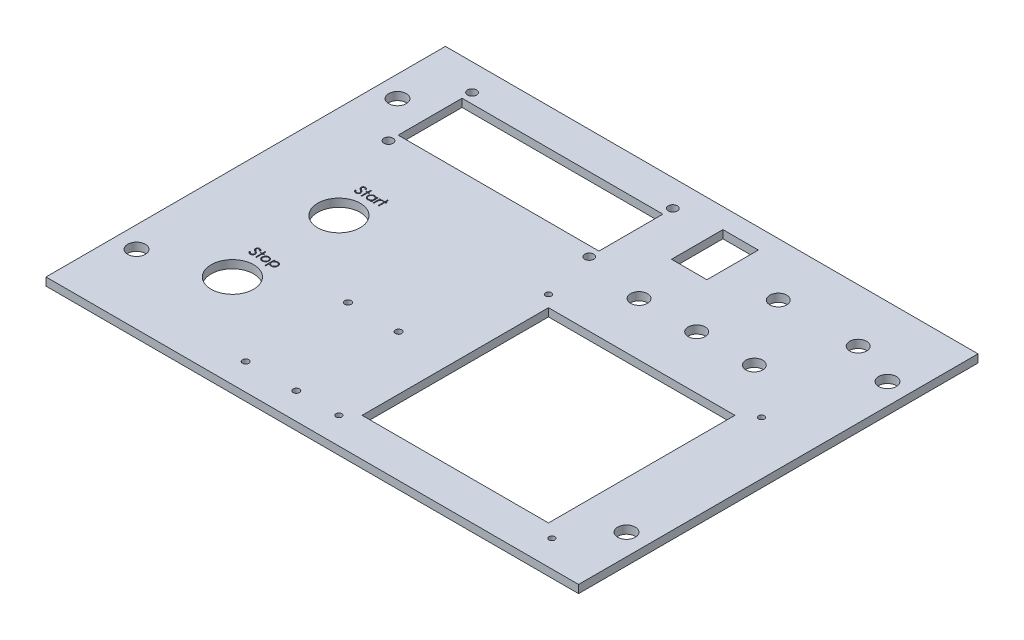
SolidWorks part; units mm, degrees
ref_plane "Front Plane" through (0, 0, 0) normal (0, 0, 1) x (1, 0, 0)
ref_plane "Top Plane" through (0, 0, 0) normal (0, 1, 0) x (1, 0, 0)
ref_plane "Right Plane" through (0, 0, 0) normal (1, 0, 0) x (0, 0, -1)
sketch "Sketch1" plane through (0, 0, 0) normal (0, 1, 0) x (1, 0, 0)
  line L1 (0, 0) -> (200, 0)
  line L2 (0, 0) -> (0, 150)
  line L3 (0, 150) -> (200, 150)
  line L4 (200, 0) -> (200, 150)
  dimension "D1" = 150
  dimension "D2" = 200
extrude "Boss-Extrude1" add sketch "Sketch1" along normal blind 3
sketch "Sketch2" plane through (0, 3, 0) normal (0, 1, 0) x (1, 0, 0)
  line L0 (100, 150) -> (100, 0) construction
  line L1 (200, 150) -> (0, 150) construction
  line L2 (0, 0) -> (200, 0) construction
  line L3 (0, 75) -> (200, 75) construction
  line L4 (0, 150) -> (0, 0) construction
  line L5 (200, 0) -> (200, 150) construction
  line L11 (111.7, 142.5) -> (125, 142.5)
  line L12 (111.7, 142.5) -> (111.7, 123.2)
  line L13 (111.7, 123.2) -> (125, 123.2)
  line L14 (125, 142.5) -> (125, 123.2)
  line L15 (111.7, 142.5) -> (125, 123.2) construction
  line L16 (111.7, 123.2) -> (125, 142.5) construction
  line L17 (65, 48.4) -> (84, 48.4) construction
  line L18 (65, 48.4) -> (65, 10) construction
  line L19 (65, 10) -> (84, 10) construction
  line L20 (84, 48.4) -> (84, 10) construction
  line L21 (100, 88.7) -> (180, 88.7) construction
  line L22 (100, 88.7) -> (100, 10) construction
  line L23 (100, 10) -> (180, 10) construction
  line L24 (180, 88.7) -> (180, 10) construction
  line L25 (104.35, 84.35) -> (174.35, 84.35)
  line L26 (104.35, 84.35) -> (104.35, 14.35)
  line L27 (104.35, 14.35) -> (174.35, 14.35)
  line L28 (174.35, 84.35) -> (174.35, 14.35)
  line L38 (20, 108.6) -> (95.4, 108.6) construction
  line L39 (20, 108.6) -> (20, 140) construction
  line L40 (20, 140) -> (95.4, 140) construction
  line L41 (95.4, 108.6) -> (95.4, 140) construction
  line L42 (95.4, 136.25) -> (20, 136.25)
  line L43 (95.4, 136.25) -> (95.4, 112.25)
  line L44 (95.4, 112.25) -> (20, 112.25)
  line L45 (20, 136.25) -> (20, 112.25)
  circle A0 centre (8, 124) radius 3.3
  circle A1 centre (8, 26) radius 3.3
  circle A2 centre (192, 26) radius 3.3
  circle A3 centre (192, 124) radius 3.3
  circle A8 centre (65, 48.4) radius 1.2
  circle A9 centre (84, 48.4) radius 1.2
  circle A10 centre (65, 10) radius 1.2
  circle A11 centre (84, 10) radius 1.2
  circle A12 centre (100, 88.7) radius 1.1
  circle A13 centre (180, 88.7) radius 1.1
  circle A14 centre (180, 10) radius 1.1
  circle A15 centre (100, 10) radius 1.1
  circle A17 centre (35, 35) radius 7.985
  circle A18 centre (35, 75) radius 7.985
  circle A19 centre (145, 130) radius 3.175
  circle A20 centre (175, 130) radius 3.175
  circle A21 centre (20, 140) radius 1.7
  circle A22 centre (95.4, 140) radius 1.7
  circle A23 centre (95.4, 108.6) radius 1.7
  circle A24 centre (20, 108.6) radius 1.7
  circle A25 centre (140, 104.35) radius 3.175
  circle A26 centre (161.65, 104.35) radius 3.175
  circle A27 centre (118.35, 104.35) radius 3.175
  point P28 (118.35, 132.85)
  point P62 (55.6115, 124.4742)
  dimension "D1" = 6.6
  dimension "D6" = 10
  dimension "D8" = 2.4
  dimension "D14" = 2.2
  dimension "D19" = 10
  dimension "D23" = 15.97
  dimension "D32" = 6.35
  dimension "D36" = 3.4
  dimension "D37" = 3.4
  dimension "D38" = 3.4
  dimension "D39" = 3.4
  dimension "D31" = 21.65
  dimension "D40" = 21.65
  dimension "D41" = 20
  dimension "D2" = 8
  dimension "D3" = 26
  dimension "D4" = 19
  dimension "D5" = 38.4
  dimension "D7" = 75.4
  dimension "D9" = 19.3
  dimension "D10" = 13.3
  dimension "D11" = 7.5
  dimension "D12" = 78.7
  dimension "D13" = 80
  dimension "D15" = 20
  dimension "D16" = 10
  dimension "D17" = 4.35
  dimension "D18" = 31.4
  dimension "D20" = 40
  dimension "D21" = 75
  dimension "D22" = 0
  dimension "D24" = 70
  dimension "D25" = 70
  dimension "D26" = 4.35
  dimension "D27" = 35
  dimension "D28" = 20
  dimension "D29" = 24
  dimension "D30" = 7.5
  dimension "D33" = 30
  dimension "D34" = 25
  dimension "D35" = 20
extrude "Cut-Extrude1" cut sketch "Sketch2" against normal up to surface (3 mm away) up to face at (100, 0, -75)
sketch "Sketch3" plane through (0, 3, 0) normal (0, 1, 0) x (1, 0, 0)
  text T0 "Start"
  text T1 "Stop"
extrude "Cut-Extrude2" cut sketch "Sketch3" against normal blind 1
